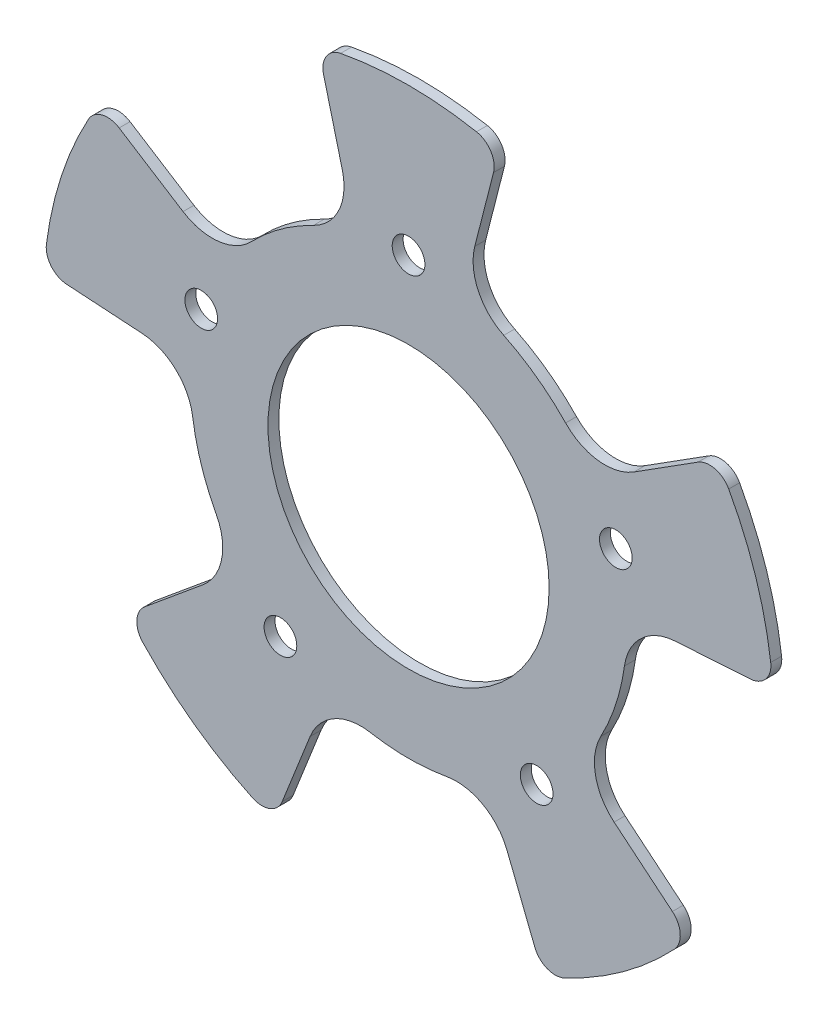
SolidWorks part; units mm, degrees
ref_plane "前视基准面" through (0, 0, 0) normal (0, 0, 1) x (1, 0, 0)
ref_plane "上视基准面" through (0, 0, 0) normal (0, 1, 0) x (1, 0, 0)
ref_plane "右视基准面" through (0, 0, 0) normal (1, 0, 0) x (0, 0, -1)
sketch "草图1" plane through (0, 0, 0) normal (0, 0, 1) x (1, 0, 0)
  line L0 (-26.6296, -8.6525) -> (0, -28) construction
  line L1 (-13.3148, -18.3262) -> (-4.9931, -6.8724) construction
  line L2 (0, 0) -> (-15.4017, -12.7588) construction
  line L3 (-15.4017, -12.7588) -> (-28.9965, -24.0208) construction
  line L4 (0, 0) -> (-7.375, -18.5906) construction
  line L5 (-7.375, -18.5906) -> (-15.6576, -39.4691) construction
  line L6 (-24.2087, -20.0546) -> (-18.8632, -15.6263)
  line L7 (-11.5922, -29.2211) -> (-9.0325, -22.7687)
  line L8 (-31.3731, 1.995) -> (-24.4455, 1.5545)
  line L9 (-26.554, 16.8267) -> (-20.6905, 13.1111)
  line L10 (-7.7975, 30.4541) -> (-6.0757, 23.7294)
  line L11 (7.7975, 30.4541) -> (6.0757, 23.7294)
  line L12 (26.554, 16.8267) -> (20.6905, 13.1111)
  line L13 (31.3731, 1.995) -> (24.4455, 1.5545)
  line L14 (24.2087, -20.0546) -> (18.8632, -15.6263)
  line L15 (11.5922, -29.2211) -> (9.0325, -22.7687)
  circle A0 centre (0, 0) radius 33.5 construction
  circle A1 centre (0, 0) radius 12.9
  circle A2 centre (0, -28) radius 2 construction
  circle A3 centre (-26.6296, -8.6525) radius 2 construction
  circle A4 centre (-16.458, 22.6525) radius 2 construction
  circle A5 centre (16.458, 22.6525) radius 2 construction
  circle A6 centre (26.6296, -8.6525) radius 2 construction
  circle A7 centre (0, 0) radius 20 construction
  circle A8 centre (-11.7557, -16.1803) radius 1.5
  circle A13 centre (-19.0211, 6.1803) radius 1.5
  circle A14 centre (0, 20) radius 1.5
  circle A15 centre (19.0211, 6.1803) radius 1.5
  circle A16 centre (11.7557, -16.1803) radius 1.5
  circle A17 centre (-26.6296, -8.6525) radius 4.6 construction
  circle A18 centre (-11.7557, -16.1803) radius 5 construction
  arc A19 (-15.4017, -12.7588) -> (-7.375, -18.5906) centre (-11.7557, -16.1803) ccw construction
  circle A20 centre (-19.0211, 6.1803) radius 5 construction
  arc A21 (-19.8103, -2.7484) -> (-17.6423, -9.4207) centre (0, 0) ccw
  arc A22 (-14.3053, -30.2921) -> (-24.3889, -22.9659) centre (0, 0) cw
  arc A23 (-17.6423, -9.4207) -> (-18.8632, -15.6263) centre (-22.0529, -11.7759) cw
  arc A24 (-33.23, 4.2443) -> (-29.3784, 16.0984) centre (0, 0) cw
  arc A25 (-14.4114, 13.8677) -> (-20.6905, 13.1111) centre (-18.0142, 17.3346) cw
  arc A26 (-8.7356, 17.9914) -> (-14.4114, 13.8677) centre (0, 0) ccw
  arc A27 (-6.232, 32.9152) -> (6.232, 32.9152) centre (0, 0) cw
  arc A28 (8.7356, 17.9914) -> (6.0757, 23.7294) centre (10.9194, 22.4892) cw
  arc A29 (14.4114, 13.8677) -> (8.7356, 17.9914) centre (0, 0) ccw
  arc A30 (29.3784, 16.0984) -> (33.23, 4.2443) centre (0, 0) cw
  arc A31 (19.8103, -2.7484) -> (24.4455, 1.5545) centre (24.7628, -3.4355) cw
  arc A32 (17.6423, -9.4207) -> (19.8103, -2.7484) centre (0, 0) ccw
  arc A33 (24.3889, -22.9659) -> (14.3053, -30.2921) centre (0, 0) cw
  arc A34 (3.5079, -19.69) -> (9.0325, -22.7687) centre (4.3848, -24.6125) cw
  arc A35 (-3.5079, -19.69) -> (3.5079, -19.69) centre (0, 0) ccw
  arc A36 (-33.23, 4.2443) -> (-31.3731, 1.995) centre (-31.2462, 3.991) ccw
  arc A37 (-29.3784, 16.0984) -> (-26.554, 16.8267) centre (-27.6245, 15.1373) cw
  arc A38 (-6.232, 32.9152) -> (-7.7975, 30.4541) centre (-5.86, 30.9501) ccw
  arc A39 (7.7975, 30.4541) -> (6.232, 32.9152) centre (5.86, 30.9501) ccw
  arc A40 (29.3784, 16.0984) -> (26.554, 16.8267) centre (27.6245, 15.1373) ccw
  arc A41 (31.3731, 1.995) -> (33.23, 4.2443) centre (31.2462, 3.991) ccw
  arc A42 (24.3889, -22.9659) -> (24.2087, -20.0546) centre (22.9328, -21.5948) ccw
  arc A43 (14.3053, -30.2921) -> (11.5922, -29.2211) centre (13.4512, -28.4836) cw
  arc A44 (-11.5922, -29.2211) -> (-14.3053, -30.2921) centre (-13.4512, -28.4836) cw
  arc A45 (-24.3889, -22.9659) -> (-24.2087, -20.0546) centre (-22.9328, -21.5948) cw
  arc A46 (-3.5079, -19.69) -> (-9.0325, -22.7687) centre (-4.3848, -24.6125) ccw
  arc A47 (18.8632, -15.6263) -> (17.6423, -9.4207) centre (22.0529, -11.7759) cw
  arc A48 (20.6905, 13.1111) -> (14.4114, 13.8677) centre (18.0142, 17.3346) cw
  arc A49 (-8.7356, 17.9914) -> (-6.0757, 23.7294) centre (-10.9194, 22.4892) ccw
  arc A50 (-19.8103, -2.7484) -> (-24.4455, 1.5545) centre (-24.7628, -3.4355) ccw
  circle A51 centre (0, 0) radius 28 construction
  point P83 (-12.3531, -31.1392)
  point P86 (-25.7978, -21.371)
  point P98 (-19.9597, 1.2692)
  dimension "D1" = 67
  dimension "D2" = 40
  dimension "D3" = 3
  dimension "D4" = 25.8
  dimension "D5" = 5
  dimension "D6" = 9.2
  dimension "D7" = 5
  dimension "D9" = 2
  dimension "D10" = 5
  dimension "D8" = 5
extrude "凸台-拉伸1" add sketch "草图1" along normal blind 1 contours A0
